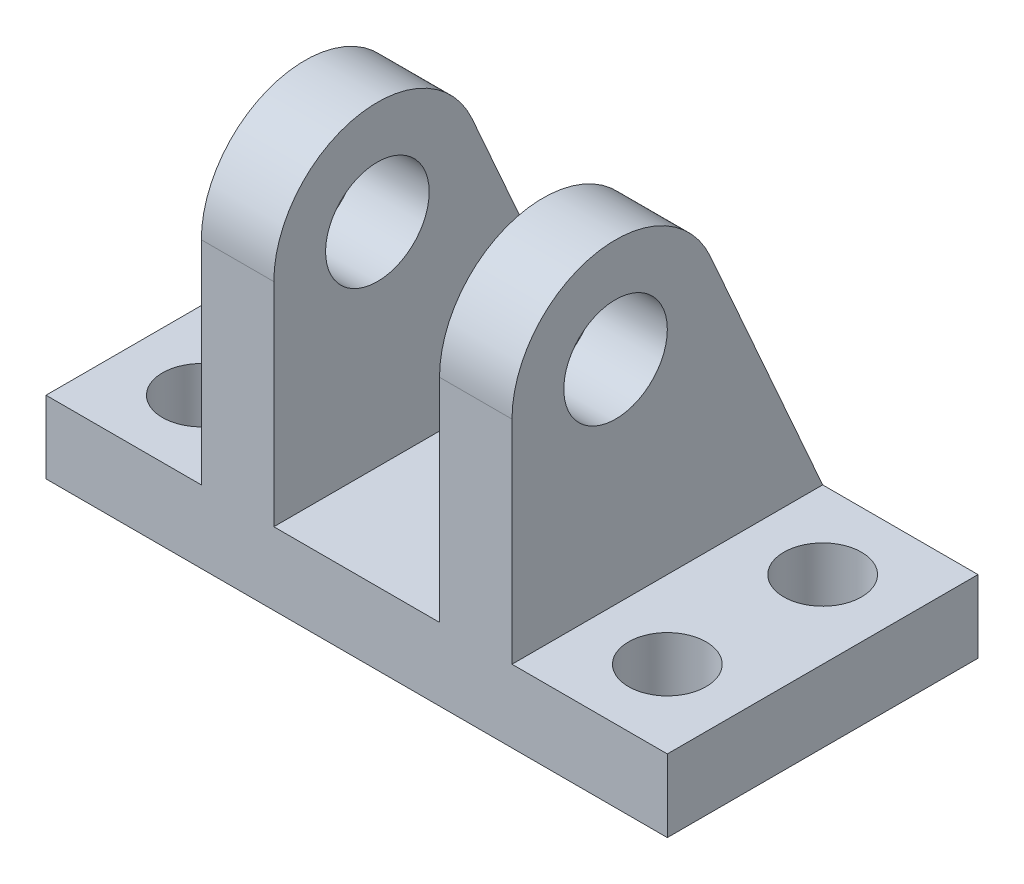
SolidWorks part; units mm, degrees
ref_plane "前视基准面" through (0, 0, 0) normal (0, 0, 1) x (1, 0, 0)
ref_plane "上视基准面" through (0, 0, 0) normal (0, 1, 0) x (1, 0, 0)
ref_plane "右视基准面" through (0, 0, 0) normal (1, 0, 0) x (0, 0, -1)
other "质心 (COM)"
sketch "草图1" plane through (0, 0, 0) normal (0, 1, 0) x (1, 0, 0)
  line L1 (-6, -6) -> (6, -6)
  line L2 (-6, -6) -> (-6, 6)
  line L3 (-6, 6) -> (6, 6)
  line L4 (6, -6) -> (6, 6)
  line L5 (-6, -6) -> (6, 6) construction
  line L6 (-6, 6) -> (6, -6) construction
  point P0 (0, 0)
  dimension "D1" = 12
  dimension "D2" = 12
extrude "凸台-拉伸1" add sketch "草图1" along normal blind 15
sketch "草图2" plane through (0, 0, 6) normal (0, 0, 1) x (1, 0, 0)
  line L0 (6, 15) -> (6, 0) construction
  line L1 (-3.2, 15) -> (3.2, 15)
  line L2 (-3.2, 15) -> (-3.2, 2.8)
  line L3 (-3.2, 2.8) -> (3.2, 2.8)
  line L4 (3.2, 15) -> (3.2, 2.8)
  line L5 (-6, 15) -> (-6, 0) construction
  line L6 (-6, 0) -> (6, 0) construction
  line L7 (-6, 15) -> (6, 15) construction
  dimension "D1" = 2.8
  dimension "D2" = 2.8
  dimension "D3" = 2.8
extrude "切除-拉伸1" cut sketch "草图2" against normal blind 12
sketch "草图3" plane through (-6, 0, 0) normal (-1, 0, 0) x (0, 0, 1)
  line L0 (-6, 15) -> (6, 15) construction
  line L1 (6, 15) -> (6, 0) construction
  line L2 (-6, 2.8) -> (6, 2.8)
  line L3 (-6, 15) -> (-6, 0) construction
  line L4 (6, 2.8) -> (6, 11)
  line L5 (-6, 2.8) -> (-1.6582, 12.6178)
  line L6 (-6, 0) -> (6, 0) construction
  line L7 (2, 15) -> (-6, 15)
  line L8 (-6, 15) -> (-6, 2.8)
  line L9 (2, 15) -> (6, 15)
  line L10 (6, 15) -> (6, 11)
  line L11 (6, 11) -> (5.9917, 7.9956)
  circle A0 centre (2, 11) radius 4
  line M4 (6, 15) -> (-6, 15)
  line M5 (-6, 15) -> (-6, 0)
  dimension "D1" = 8
  dimension "D2" = 2.8
extrude "切除-拉伸2" cut sketch "草图3" against normal blind 12 contours A0 L5 M4 M5 | A0 L10 M4
sketch "草图4" plane through (-6, 0, 0) normal (-1, 0, 0) x (0, 0, 1)
  circle A0 centre (2, 11) radius 1.9653
  dimension "D1" = 3.9306
sketch "草图8" plane through (6, 0, 0) normal (1, 0, 0) x (0, 0, -1)
  circle A0 centre (-2, 11) radius 2
  dimension "D1" = 4
extrude "切除-拉伸3" cut sketch "草图8" against normal through all
sketch "草图10" plane through (0, 0, 0) normal (0, 1, 0) x (1, 0, 0)
  line L0 (-3.2, -6) -> (-6, -6) construction
  line L1 (-6, 6) -> (-12, 6)
  line L2 (-6, 6) -> (-6, -6)
  line L3 (-6, -6) -> (-12, -6)
  line L4 (-12, 6) -> (-12, -6)
  line L5 (6, -6) -> (3.2, -6) construction
  line L6 (6, 6) -> (12, 6)
  line L7 (6, 6) -> (6, -6)
  line L8 (6, -6) -> (12, -6)
  line L9 (12, 6) -> (12, -6)
  circle A0 centre (-9, 3) radius 1.5
  circle A1 centre (-9, -3) radius 1.5
  circle A2 centre (9, 3) radius 1.5
  circle A3 centre (9, -3) radius 1.5
  dimension "D2" = 3
  dimension "D3" = 3
  dimension "D5" = 3
  dimension "D8" = 3
  dimension "D10" = 3
  dimension "D1" = 6
  dimension "D4" = 3
  dimension "D6" = 3
  dimension "D7" = 6
  dimension "D9" = 3
extrude "凸台-拉伸2" add sketch "草图10" along normal up to surface (2.8 mm away) up to face at (0, 2.8, 0)
